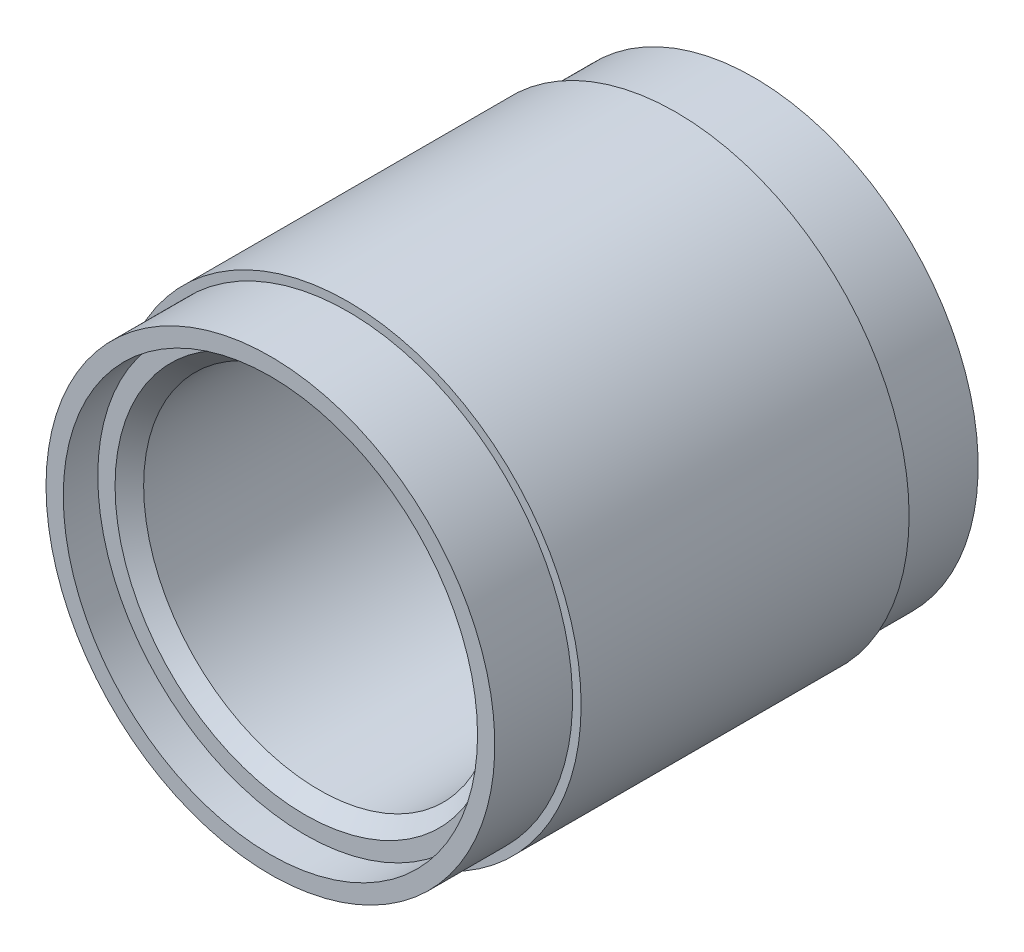
SolidWorks part; units mm, degrees
material "Сталь 12Х17 ГОСТ 5632-72"
ref_plane "Спереди" through (0, 0, 0) normal (0, 0, 1) x (1, 0, 0)
ref_plane "Сверху" through (0, 0, 0) normal (0, 1, 0) x (1, 0, 0)
ref_plane "Справа" through (0, 0, 0) normal (1, 0, 0) x (0, 0, -1)
sketch "Эскиз2" plane through (0, 0, 0) normal (0, 0, 1) x (1, 0, 0)
  circle A0 centre (0, 0) radius 13
  dimension "D1" = 26
extrude "Бобышка-Вытянуть1" add sketch "Эскиз2" along normal blind 4.5
sketch "Эскиз3" plane through (0, 0, 4.5) normal (0, 0, 1) x (1, 0, 0)
  circle A0 centre (0, 0) radius 13.5
  dimension "D1" = 27
extrude "Бобышка-Вытянуть2" add sketch "Эскиз3" along normal blind 9.5
sketch "Эскиз4" plane through (0, 0, 0) normal (0, 0, -1) x (-1, 0, 0)
  circle A0 centre (0, 0) radius 12
  dimension "D1" = 24
extrude "Вырез-Вытянуть1" cut sketch "Эскиз4" against normal blind 2
mirror "Зеркальное отражение4" about plane through (0, 0, 14) normal (0, 0, 1) of bodies 107
sketch "Эскиз5" plane through (0, 0, 2) normal (0, 0, -1) x (-1, 0, 0)
  circle A0 centre (0, 0) radius 10.172
  dimension "D1" = 20.344
extrude "Вырез-Вытянуть2" cut sketch "Эскиз5" against normal through all
cosmetic thread "Условное изображение резьбы1" parameters "D2"=22
chamfer "Фаска1" distance 0.828 angle 45 2 edges at (10.172, 0, 26) (-10.172, 0, 2)
